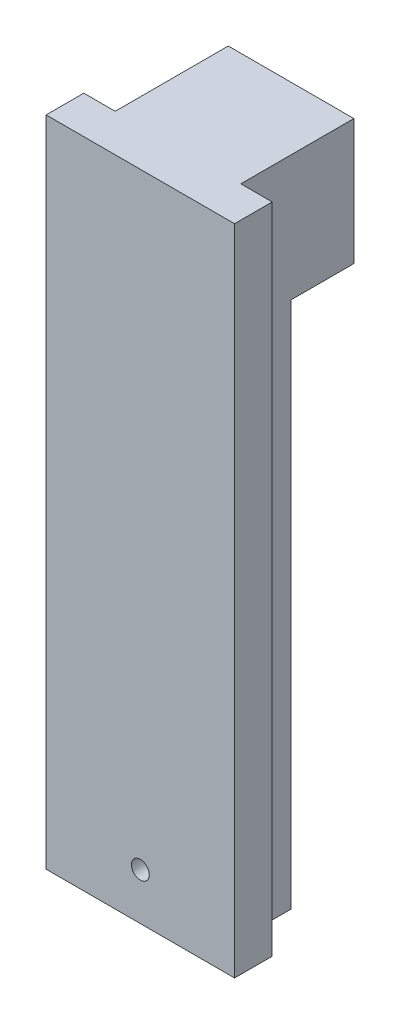
SolidWorks part; units mm, degrees
ref_plane "Płaszczyzna przednia" through (0, 0, 0) normal (0, 0, 1) x (1, 0, 0)
ref_plane "Płaszczyzna górna" through (0, 0, 0) normal (0, 1, 0) x (1, 0, 0)
ref_plane "Płaszczyzna prawa" through (0, 0, 0) normal (1, 0, 0) x (0, 0, -1)
sketch "Szkic1" plane through (0, 0, 0) normal (0, 1, 0) x (1, 0, 0)
  line L0 (0, -6) -> (0, 0) construction
  line L1 (0, 14) -> (0, 0) construction
  line L7 (-15, 0) -> (15, 0)
  line L8 (20, 6) -> (10, 6) construction
  line L10 (15, 0) -> (15, 6)
  line L11 (15, 6) -> (10, 6)
  line L12 (10, 6) -> (10, 14)
  line L13 (10, 14) -> (-10, 14)
  line L14 (-10, 14) -> (-10, 6)
  line L15 (-10, 6) -> (-15, 6)
  line L16 (-15, 6) -> (-15, 0)
  point P2 (0, 0)
  point P3 (10, 3)
  dimension "D1" = 6
  dimension "D4" = 10
  dimension "D5" = 30
  dimension "D6" = 20
  dimension "D7" = 6
  dimension "D8" = 5
  dimension "D9" = 30
  dimension "D10" = 20
  dimension "D11" = 20
  dimension "D12" = 8
  dimension "D13" = 6
extrude "Dodanie-wyciągnięcie1" add sketch "Szkic1" along normal blind 104
sketch "Szkic2" plane through (0, 0, -14) normal (0, 0, -1) x (-1, 0, 0)
  line L0 (-10, 104) -> (10, 104)
  line L1 (10, 104) -> (10, 84)
  line L2 (10, 104) -> (10, 0) construction
  line L3 (10, 84) -> (-10, 84)
  line L4 (-10, 104) -> (-10, 0) construction
  line L5 (-10, 84) -> (-10, 104)
  dimension "D1" = 20
extrude "Dodanie-wyciągnięcie2" add sketch "Szkic2" along normal blind 10
sketch "Szkic3" plane through (0, 0, -24) normal (0, 0, -1) x (-1, 0, 0)
  line L0 (-10, 94) -> (10, 94) construction
  line L1 (-10, 104) -> (-10, 84) construction
  line L2 (10, 84) -> (10, 104) construction
  line L3 (0, 104) -> (0, 84) construction
  line L4 (10, 104) -> (-10, 104) construction
  line L5 (-10, 84) -> (10, 84) construction
  circle A0 centre (0, 94) radius 2.5
  dimension "D1" = 5
extrude "Wytnij-wyciągnięcie1" cut sketch "Szkic3" against normal blind 10
sketch "Szkic4" plane through (0, 0, 0) normal (0, 0, 1) x (1, 0, 0)
  line L0 (0, 0) -> (0, 6) construction
  circle A0 centre (0, 7.425) radius 1.425
  point P5 (0, 0)
  dimension "D2" = 2.85
  dimension "D1" = 6
extrude "Wytnij-wyciągnięcie2" cut sketch "Szkic4" against normal through all
